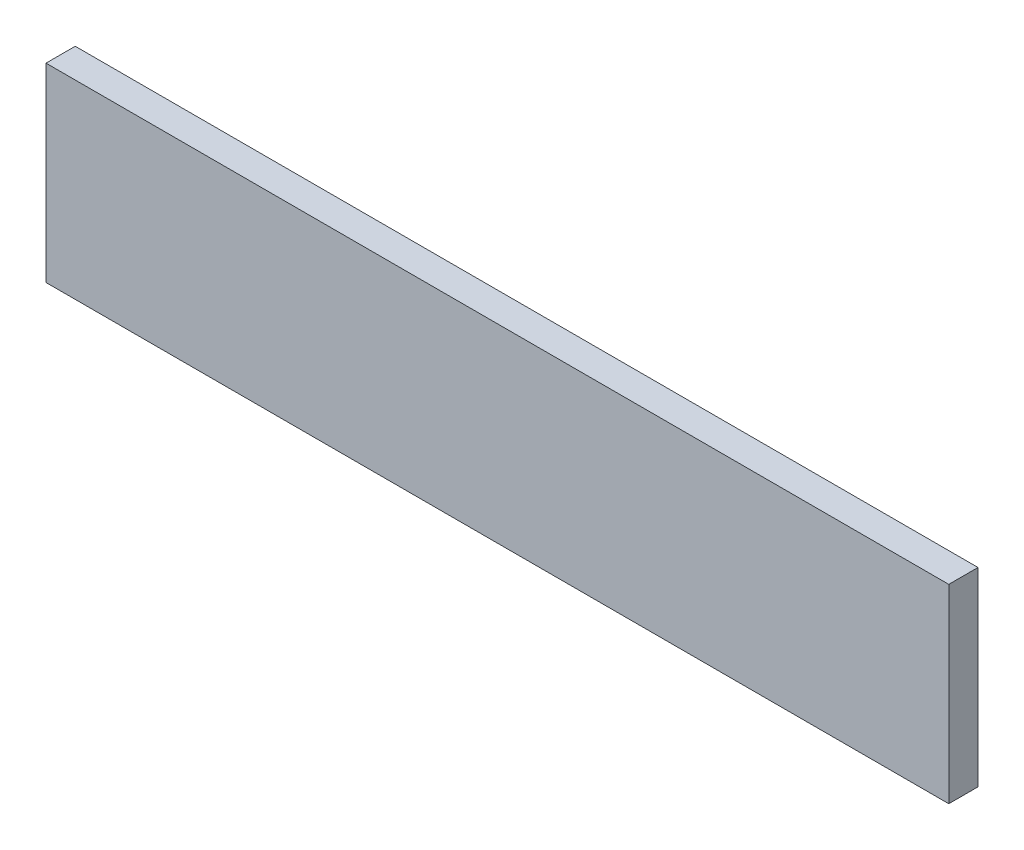
SolidWorks part; units mm, degrees
ref_plane "Plan de face" through (0, 0, 0) normal (0, 0, 1) x (1, 0, 0)
ref_plane "Plan de dessus" through (0, 0, 0) normal (0, 1, 0) x (1, 0, 0)
ref_plane "Plan de droite" through (0, 0, 0) normal (1, 0, 0) x (0, 0, -1)
sketch "Esquisse1" plane through (0, 0, 0) normal (0, 0, 1) x (1, 0, 0)
  line L1 (-196.1081, 41.275) -> (196.1081, 41.275)
  line L2 (-196.1081, 41.275) -> (-196.1081, -41.275)
  line L3 (-196.1081, -41.275) -> (196.1081, -41.275)
  line L4 (196.1081, 41.275) -> (196.1081, -41.275)
  line L5 (-196.1081, 41.275) -> (196.1081, -41.275) construction
  line L6 (-196.1081, -41.275) -> (196.1081, 41.275) construction
  point P0 (0, 0)
  dimension "D1" = 82.55
  dimension "D2" = 392.2161
extrude "Boss.-Extru.1" add sketch "Esquisse1" along normal blind 12.7
